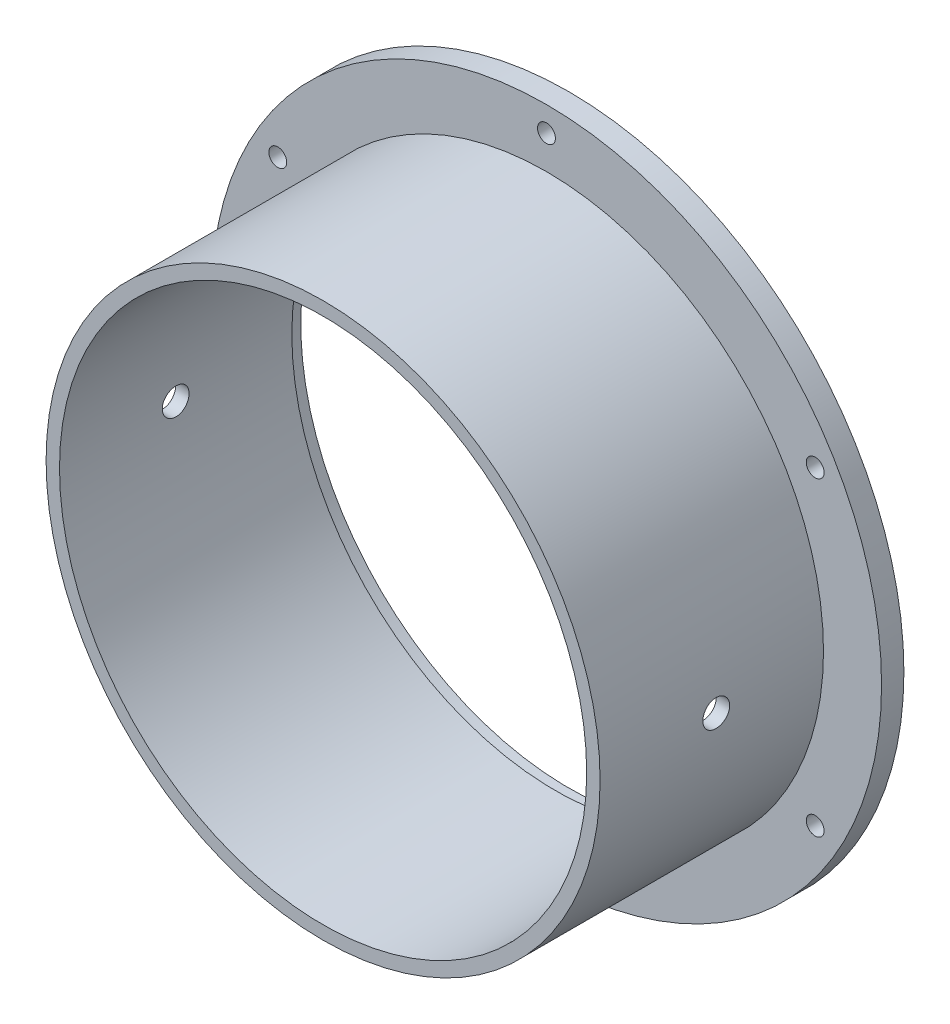
SolidWorks part; units mm, degrees
ref_plane "Спереди" through (0, 0, 0) normal (0, 0, 1) x (1, 0, 0)
ref_plane "Сверху" through (0, 0, 0) normal (0, 1, 0) x (1, 0, 0)
ref_plane "Справа" through (0, 0, 0) normal (1, 0, 0) x (0, 0, -1)
sketch "Эскиз1" plane through (0, 0, 0) normal (0, 0, 1) x (1, 0, 0)
  circle A0 centre (0, 0) radius 75
  circle A1 centre (0, 0) radius 60
extrude "Бобышка-Вытянуть1" add sketch "Эскиз1" along normal blind 5
sketch "Эскиз2" plane through (0, 0, 5) normal (0, 0, 1) x (1, 0, 0)
  circle A0 centre (0, 0) radius 62
  circle A1 centre (0, 0) radius 59
extrude "Бобышка-Вытянуть2" add sketch "Эскиз2" along normal blind 50 and the other way blind 2 separate body
sketch "Эскиз3" plane through (0, 0, 5) normal (0, 0, 1) x (1, 0, 0)
  line L0 (0, -925) -> (0, 49075) construction
  circle A1 centre (0, 69.4428) radius 2
  circle A2 centre (60.1392, 34.7214) radius 2
  circle A3 centre (60.1392, -34.7214) radius 2
  circle A4 centre (0, -69.4428) radius 2
  circle A5 centre (-60.1392, -34.7214) radius 2
  circle A6 centre (-60.1392, 34.7214) radius 2
  point P17 (0, 0)
  dimension "D1" = 6
extrude "Вырез-Вытянуть1" cut sketch "Эскиз3" against normal through all
sketch "Эскиз5" plane through (0, 0, 0) normal (1, 0, 0) x (0, 0, -1)
  line L0 (-29, -938) -> (-29, 49062) construction
  line L1 (-3, 62) -> (-55, 62) construction
  line L2 (-1055, 0) -> (48945, 0) construction
  line L3 (-55, 62) -> (-55, -62) construction
  circle A0 centre (-29, 0) radius 3
  point P5 (-29, 62)
  point P10 (-55, 0)
extrude "Вырез-Вытянуть2" cut sketch "Эскиз5" against normal through all and the other way through all
